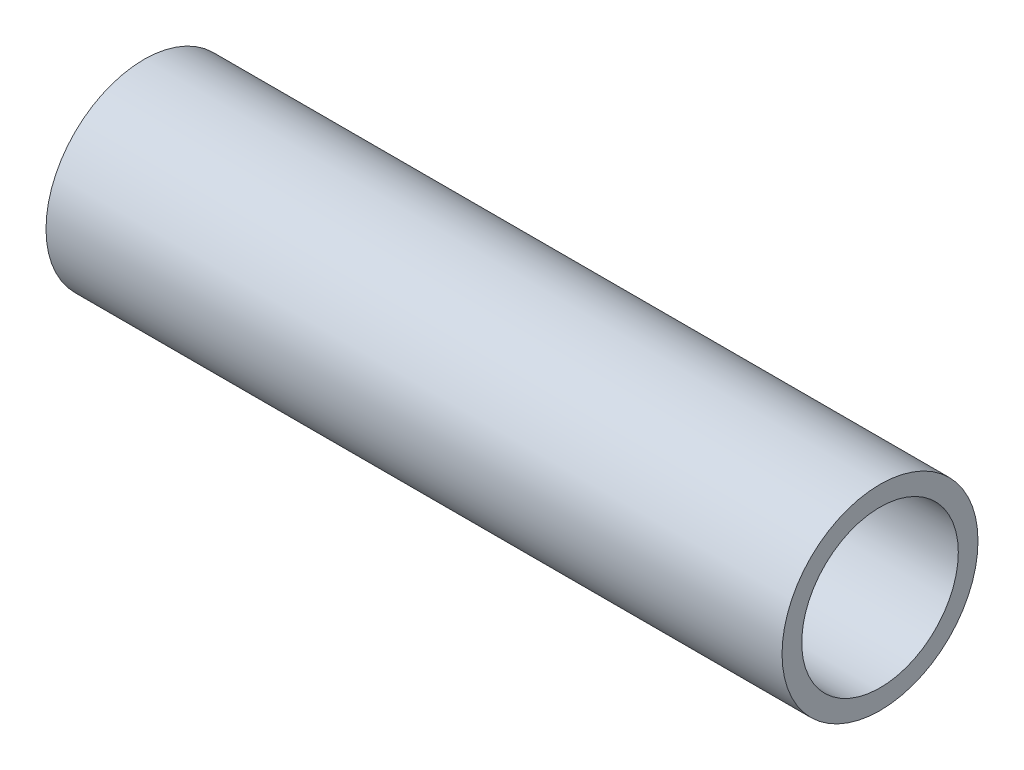
SolidWorks part; units mm, degrees
material "PVC Rígido"
ref_plane "Alzado" through (0, 0, 0) normal (0, 0, 1) x (1, 0, 0)
ref_plane "Planta" through (0, 0, 0) normal (0, 1, 0) x (1, 0, 0)
ref_plane "Vista lateral" through (0, 0, 0) normal (1, 0, 0) x (0, 0, -1)
sketch "Croquis1" plane through (0, 0, 0) normal (1, 0, 0) x (0, 0, -1)
  circle A0 centre (0, 0) radius 10.65
  circle A1 centre (0, 0) radius 8.51
  dimension "D1" = 17.02
  dimension "D2" = 21.3
extrude "Saliente-Extruir1" add sketch "Croquis1" along normal blind 80
